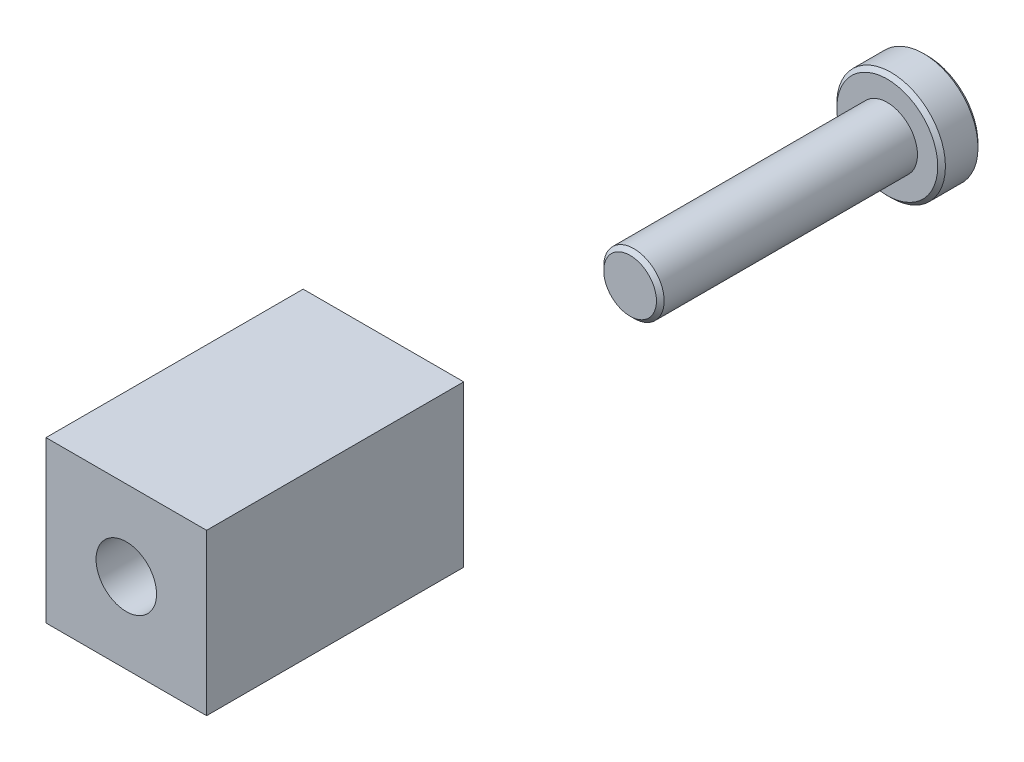
SolidWorks part; units mm, degrees
ref_plane "Front Plane" through (0, 0, 0) normal (0, 0, 1) x (1, 0, 0)
ref_plane "Top Plane" through (0, 0, 0) normal (0, 1, 0) x (1, 0, 0)
ref_plane "Right Plane" through (0, 0, 0) normal (1, 0, 0) x (0, 0, -1)
sketch "Sketch1" plane through (0, 0, 0) normal (0, 0, 1) x (1, 0, 0)
  circle A0 centre (0, 0) radius 10.7315
  dimension "D1" = 21.463
extrude "Boss-Extrude1" add sketch "Sketch1" along normal blind 7.9587
sketch "Sketch2" plane through (0, 0, 7.9587) normal (0, 0, 1) x (1, 0, 0)
  circle A0 centre (0, 0) radius 5.969
  dimension "D1" = 11.938
extrude "Boss-Extrude2" add sketch "Sketch2" along normal blind 50.8
ref_plane "Plane1" through (0, 0, 107.4833) normal (0, 0, 1) x (1, 0, 0)
sketch "Sketch3" plane through (0, 0, 107.4833) normal (0, 0, 1) x (1, 0, 0)
  line L0 (15.8613, -15.8613) -> (-15.8613, 15.8613) construction
  line L1 (-15.8613, 15.8613) -> (15.8613, 15.8613)
  line L2 (-15.8613, 15.8613) -> (-15.8613, -15.8613)
  line L3 (-15.8613, -15.8613) -> (15.8613, -15.8613)
  line L4 (15.8613, 15.8613) -> (15.8613, -15.8613)
extrude "Boss-Extrude3" add sketch "Sketch3" along normal blind 50.8 separate body
sketch "Sketch4" plane through (0, 0, 107.4833) normal (0, 0, -1) x (-1, 0, 0)
  circle A0 centre (0, 0) radius 5.9753
  dimension "D1" = 11.9507
extrude "Cut-Extrude1" cut sketch "Sketch4" against normal through all
chamfer "Chamfer1" distance 0.762 angle 45 3 edges at (10.7315, 0, 0) (10.7315, 0, 7.9587) (5.969, 0, 58.7587)
equation "\"Pin Shaft Diameter\" = 0.47"
equation "\"Base Length\"= \"D1@Boss-Extrude3\""
equation "\"D1@Sketch1\"= \"Pin Shaft Diameter\" + 0.375"
equation "\"D1@Boss-Extrude1\"= \"Pin Shaft Diameter\" / 1.5"
equation "\"D1@Boss-Extrude2\"= \"Base Length\""
equation "\"D1@Sketch4\"= \"Pin Shaft Diameter\" + 0.0005"
equation "\"D1@Sketch2\"= \"Pin Shaft Diameter\""
